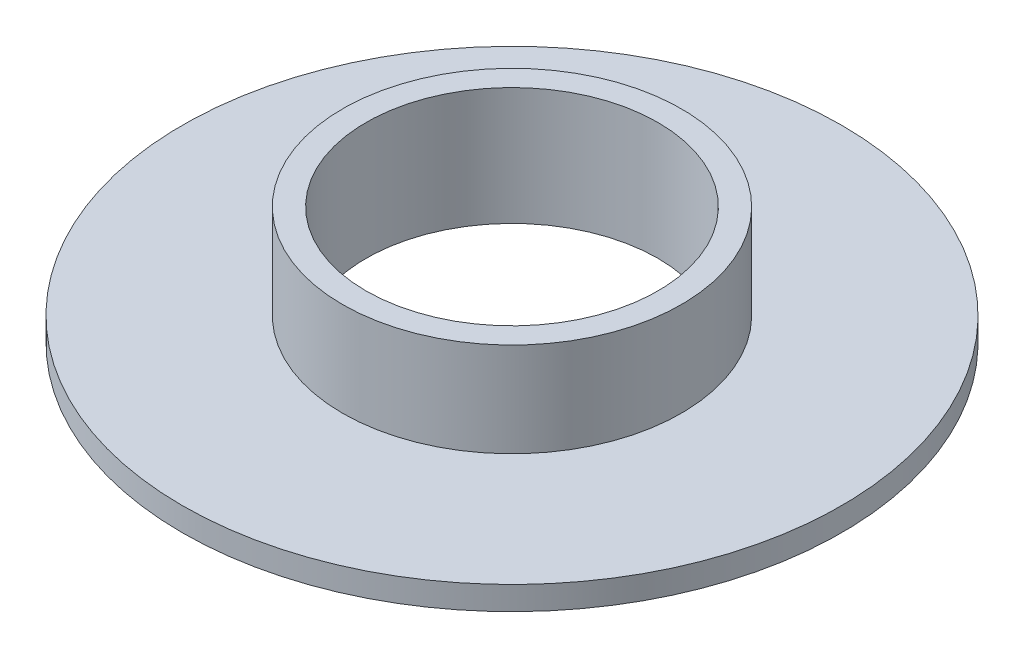
SolidWorks part; units mm, degrees
ref_plane "Front Plane" through (0, 0, 0) normal (0, 0, 1) x (1, 0, 0)
ref_plane "Top Plane" through (0, 0, 0) normal (0, 1, 0) x (1, 0, 0)
ref_plane "Right Plane" through (0, 0, 0) normal (1, 0, 0) x (0, 0, -1)
sketch "Sketch1" plane through (0, 0, 0) normal (1, 0, 0) x (0, 0, -1)
  line L0 (0, 0) -> (70, 0)
  line L1 (70, 0) -> (70, 5)
  line L2 (70, 5) -> (36, 5)
  line L3 (36, 5) -> (36, 25)
  line L4 (36, 25) -> (31, 25)
  line L5 (31, 25) -> (31, 5)
  line L6 (31, 5) -> (0, 5)
  line L7 (0, 5) -> (0, 0)
  dimension "D1" = 5
  dimension "D2" = 36
  dimension "D3" = 70
  dimension "D4" = 5
  dimension "D5" = 20
revolve "Revolve1" add sketch "Sketch1" angle 360 about L7
sketch "Sketch3" plane through (0, 5, 0) normal (0, 1, 0) x (1, 0, 0)
  circle A0 centre (0, 0) radius 31
extrude "Cut-Extrude1" cut sketch "Sketch3" against normal blind 10
